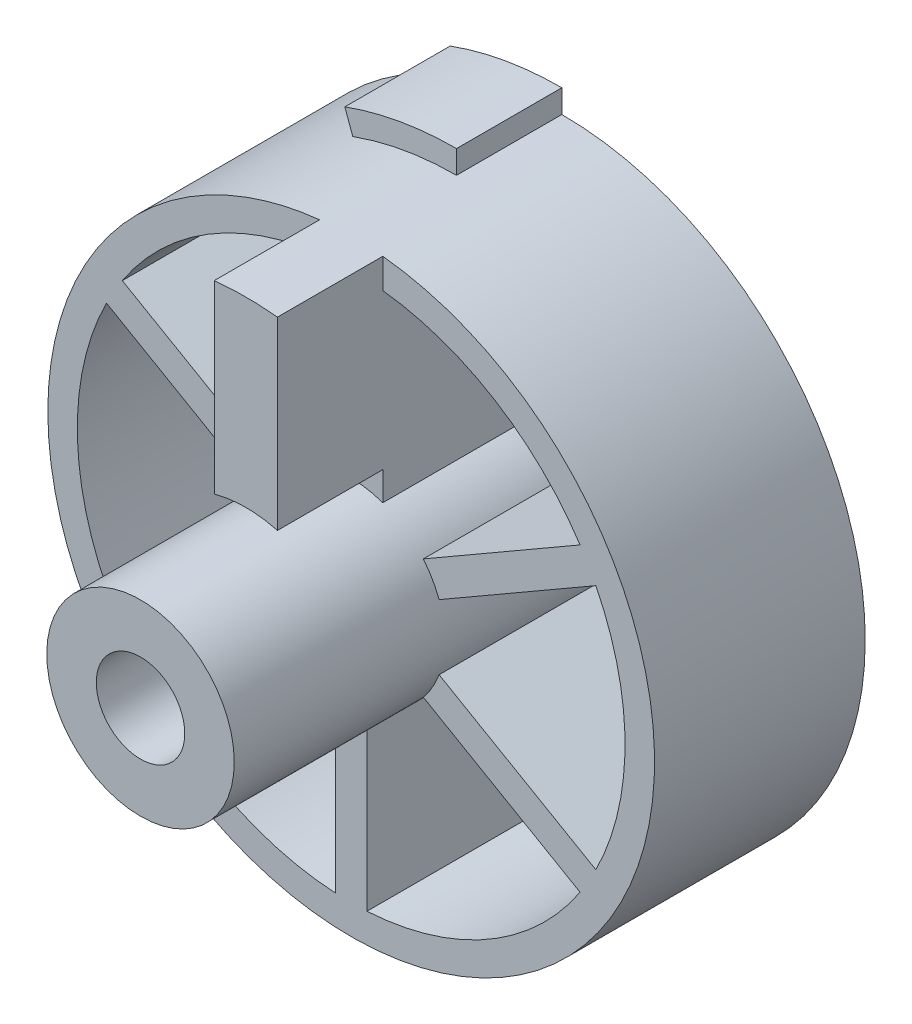
SolidWorks part; units mm, degrees
ref_plane "前视基准面" through (0, 0, 0) normal (0, 0, 1) x (1, 0, 0)
ref_plane "上视基准面" through (0, 0, 0) normal (0, 1, 0) x (1, 0, 0)
ref_plane "右视基准面" through (0, 0, 0) normal (1, 0, 0) x (0, 0, -1)
sketch "草图1" plane through (0, 0, 0) normal (0, 0, 1) x (1, 0, 0)
  line L0 (0, 0) -> (0, 44.2551) construction
  line L1 (0, 0) -> (17101.0072, -46984.631) construction
  line L2 (0, 31) -> (0, 28.8)
  line L3 (-10.6026, 29.1305) -> (-9.8502, 27.0631)
  line L4 (0, -28.8) -> (0, -31)
  line L5 (10.6026, -29.1305) -> (9.8502, -27.0631)
  circle A0 centre (0, 0) radius 4.2
  arc A1 (9.8502, -27.0631) -> (0, 28.8) centre (0, 0) ccw
  arc A2 (0, 31) -> (-10.6026, 29.1305) centre (0, 0) ccw
  arc A3 (0, -31) -> (10.6026, -29.1305) centre (0, 0) ccw
  arc A4 (-9.8502, 27.0631) -> (0, -28.8) centre (0, 0) ccw
  dimension "D1" = 57.6
  dimension "D2" = 8.4
  dimension "D3" = 62
  dimension "D4" = 20
extrude "凸台-拉伸1" add sketch "草图1" along normal blind 10
sketch "草图2" plane through (0, 0, 10) normal (0, 0, 1) x (1, 0, 0)
  circle A0 centre (0, 0) radius 28.8
extrude "凸台-拉伸2" add sketch "草图2" along normal blind 10
sketch "草图3" plane through (0, 0, 20) normal (0, 0, 1) x (1, 0, 0)
  circle A0 centre (0, 0) radius 8.9
  dimension "D1" = 17.8
extrude "凸台-拉伸3" add sketch "草图3" along normal blind 20
sketch "草图4" plane through (0, 0, 40) normal (0, 0, 1) x (1, 0, 0)
  circle A1 centre (0, 0) radius 4.2
  dimension "D1" = 8.4
extrude "切除-拉伸1" cut sketch "草图4" against normal through all
sketch "草图5" plane through (0, 0, 20) normal (0, 0, 1) x (1, 0, 0)
  line L0 (0, 6.6214) -> (0, 50000) construction
  line L1 (21.7292, 14.2774) -> (6.8474, 5.6854)
  line L3 (-1.5, 25.9567) -> (-1.5, 8.7727)
  line L5 (1.5, 25.9567) -> (1.5, 8.7727)
  line L6 (23.2292, 11.6793) -> (8.3474, 3.0873)
  line L7 (23.2292, -11.6793) -> (8.3474, -3.0873)
  line L8 (21.7292, -14.2774) -> (6.8474, -5.6854)
  line L9 (1.5, -25.9567) -> (1.5, -8.7727)
  line L10 (-1.5, -25.9567) -> (-1.5, -8.7727)
  line L11 (-21.7292, -14.2774) -> (-6.8474, -5.6854)
  line L12 (-23.2292, -11.6793) -> (-8.3474, -3.0873)
  line L13 (-23.2292, 11.6793) -> (-8.3474, 3.0873)
  line L14 (-21.7292, 14.2774) -> (-6.8474, 5.6854)
  arc A0 (-8.3474, 3.0873) -> (-8.3474, -3.0873) centre (0, 0) ccw
  arc A1 (-23.2292, 11.6793) -> (-23.2292, -11.6793) centre (0, 0) ccw
  arc A2 (-6.8474, -5.6854) -> (-1.5, -8.7727) centre (0, 0) ccw
  arc A3 (-21.7292, -14.2774) -> (-1.5, -25.9567) centre (0, 0) ccw
  arc A4 (1.5, -25.9567) -> (21.7292, -14.2774) centre (0, 0) ccw
  arc A5 (1.5, -8.7727) -> (6.8474, -5.6854) centre (0, 0) ccw
  arc A6 (8.3474, -3.0873) -> (8.3474, 3.0873) centre (0, 0) ccw
  arc A7 (23.2292, -11.6793) -> (23.2292, 11.6793) centre (0, 0) ccw
  arc A8 (6.8474, 5.6854) -> (1.5, 8.7727) centre (0, 0) ccw
  arc A9 (21.7292, 14.2774) -> (1.5, 25.9567) centre (0, 0) ccw
  arc A10 (-1.5, 25.9567) -> (-21.7292, 14.2774) centre (0, 0) ccw
  arc A11 (-1.5, 8.7727) -> (-6.8474, 5.6854) centre (0, 0) ccw
  point P32 (0, 0)
  dimension "D1" = 52
  dimension "D2" = 6
extrude "切除-拉伸2" cut sketch "草图5" against normal through all
sketch "草图8" plane through (0, 0, 20) normal (0, 0, 1) x (1, 0, 0)
  line L0 (0, 0) -> (0, 50000) construction
  line L2 (-3, 27.1251) -> (3, 27.1251)
  line L3 (-3, 27.1251) -> (-3, 7.0837)
  line L4 (-3, 7.0837) -> (3, 7.0837)
  line L5 (3, 27.1251) -> (3, 7.0837)
  dimension "D1" = 6
extrude "凸台-拉伸4" add sketch "草图8" against normal blind 20
sketch "草图9" plane through (0, 0, 20) normal (0, 0, 1) x (1, 0, 0)
  line L2 (-3, 11.1018) -> (-3, 28.6433)
  line L4 (3, 11.1018) -> (3, 28.6433)
  circle A0 centre (0, 0) radius 28.8
  circle A1 centre (0, 0) radius 11.5
  line M2 (-3, 25.8263) -> (-3, 8.3791)
  line M4 (3, 8.3791) -> (3, 25.8263)
  circle M25 centre (0, 0) radius 28.8
  dimension "D1" = 23
  dimension "D2" = 57.6
extrude "凸台-拉伸5" add sketch "草图9" along normal blind 10 contours A1 L4 L2 M4 M25 M2
